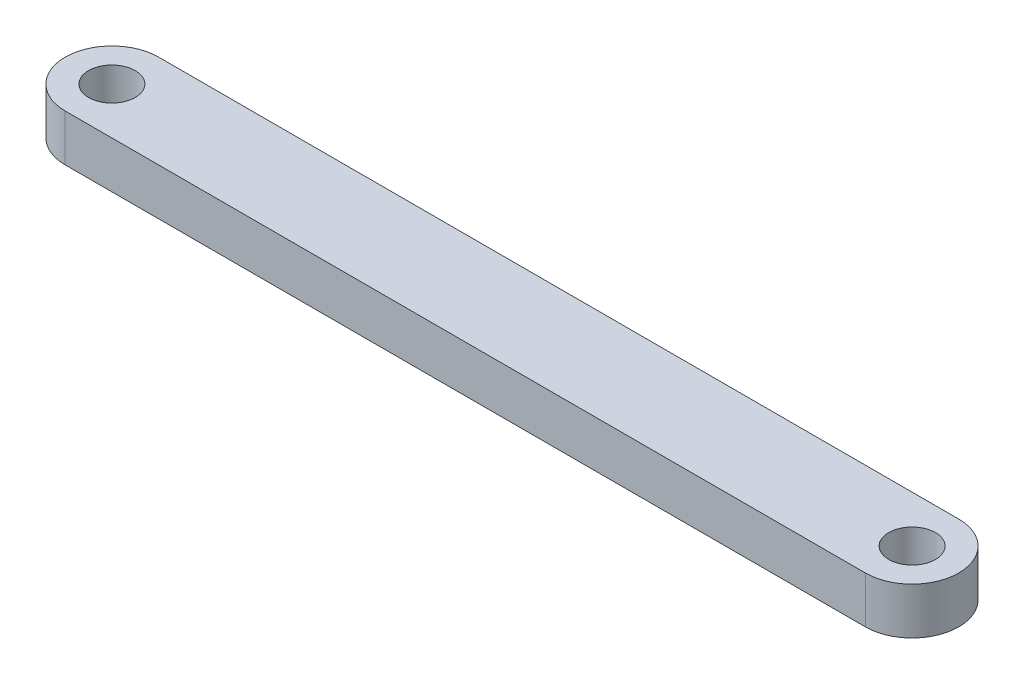
SolidWorks part; units mm, degrees
ref_plane "前视基准面" through (0, 0, 0) normal (0, 0, 1) x (1, 0, 0)
ref_plane "上视基准面" through (0, 0, 0) normal (0, 1, 0) x (1, 0, 0)
ref_plane "右视基准面" through (0, 0, 0) normal (1, 0, 0) x (0, 0, -1)
other "Configuration Table"
sketch "草图1" plane through (0, 0, 0) normal (0, 1, 0) x (1, 0, 0)
  line L0 (-17.14, 0) -> (17.14, 0) construction
  line L1 (-17.14, 2) -> (17.14, 2)
  line L2 (17.14, -2) -> (-17.14, -2)
  circle A0 centre (-17.14, 0) radius 1
  circle A1 centre (17.14, 0) radius 1
  arc A2 (-17.14, 2) -> (-17.14, -2) centre (-17.14, 0) ccw
  arc A3 (17.14, -2) -> (17.14, 2) centre (17.14, 0) ccw
  point P4 (0, 0)
  dimension "D2" = 2
  dimension "D3" = 2
  dimension "D4" = 4
  dimension "D5" = 4
  dimension "D1" = 34.28
  dimension "D6" = 34.28
extrude "凸台-拉伸1" add sketch "草图1" along normal blind 2
